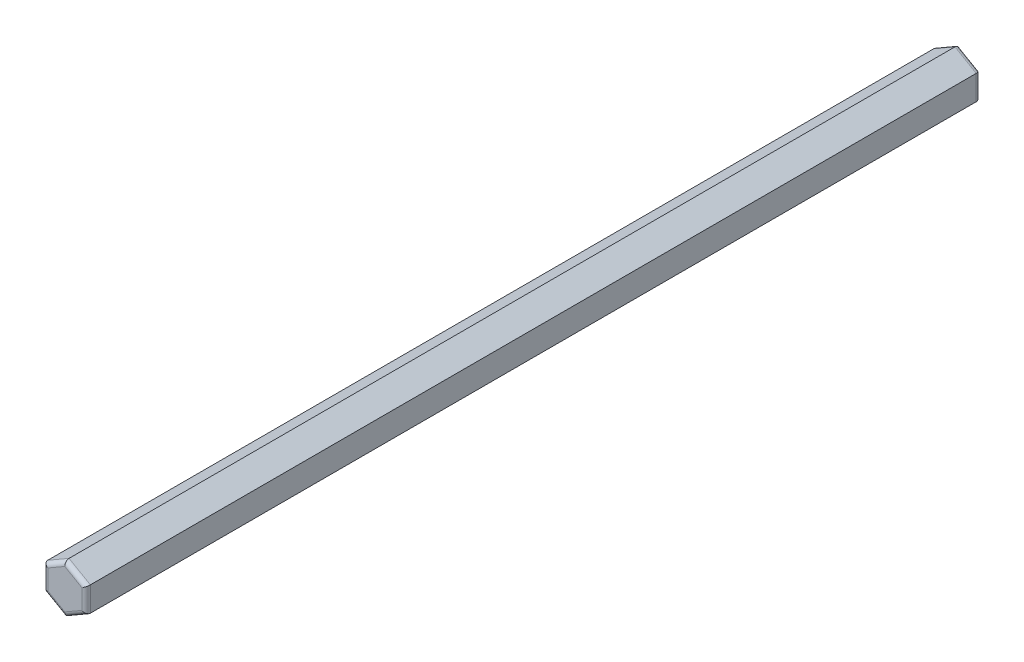
SolidWorks part; units mm, degrees
ref_plane "Plano frontal" through (0, 0, 0) normal (0, 0, 1) x (1, 0, 0)
ref_plane "Plano superior" through (0, 0, 0) normal (0, 1, 0) x (1, 0, 0)
ref_plane "Plano direito" through (0, 0, 0) normal (1, 0, 0) x (0, 0, -1)
ref_plane "Plano1" through (0, 0, 135) normal (0, 0, 1) x (1, 0, 0)
sketch "Esboço1" plane through (0, 0, 135) normal (0, 0, 1) x (1, 0, 0)
  line L0 (-55.0021, 2.8868) -> (-57.5021, 1.4434)
  line L1 (-57.5021, 1.4434) -> (-57.5021, -1.4434)
  line L2 (-57.5021, -1.4434) -> (-55.0021, -2.8868)
  line L3 (-55.0021, -2.8868) -> (-52.5021, -1.4434)
  line L4 (-52.5021, -1.4434) -> (-52.5021, 1.4434)
  line L5 (-52.5021, 1.4434) -> (-55.0021, 2.8868)
  line L6 (-55.0021, 2.8868) -> (-55.0021, -2.8868) construction
  circle A0 centre (-55.0021, 0) radius 2.8868 construction
  dimension "D1" = 5
extrude "Ressalto-extrusão1" add sketch "Esboço1" against normal blind 105
fillet "Filete1" radius 0.5 12 edges at (-53.7521, -2.1651, 135) (-56.2521, -2.1651, 135) (-52.5021, 0, 135) (-57.5021, 0, 135) (-53.7521, 2.1651, 135) (-56.2521, 2.1651, 135) (-53.7521, -2.1651, 30) (-56.2521, -2.1651, 30) (-52.5021, 0, 30) (-57.5021, 0, 30) (-53.7521, 2.1651, 30) (-56.2521, 2.1651, 30)
